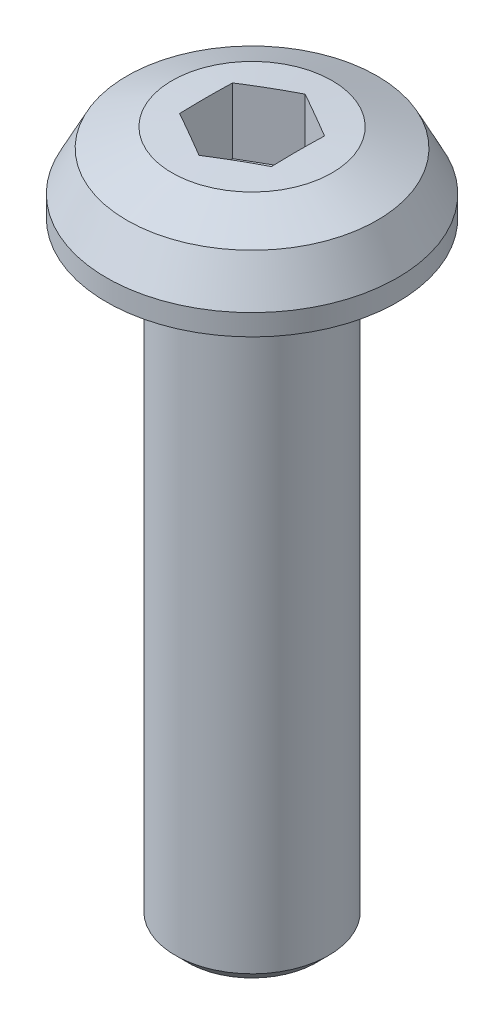
SolidWorks part; units mm, degrees
ref_plane "Front Plane" through (0, 0, 0) normal (0, 0, 1) x (1, 0, 0)
ref_plane "Top Plane" through (0, 0, 0) normal (0, 1, 0) x (1, 0, 0)
ref_plane "Right Plane" through (0, 0, 0) normal (1, 0, 0) x (0, 0, -1)
sketch "Sketch1" plane through (0, 0, 0) normal (0, 0, 1) x (1, 0, 0)
  line L0 (0, -20) -> (2.1, -20)
  line L1 (2.1, -20) -> (2.5, -19.6)
  line L2 (2.5, -19.6) -> (2.5, 0)
  line L3 (2.5, 0) -> (4.75, 0)
  line L4 (4.75, 0) -> (4.75, 0.6875)
  line L5 (4.75, 0.6875) -> (4.085, 1.98)
  line L6 (4.085, 1.98) -> (2.6125, 2.585)
  line L7 (2.6125, 2.585) -> (0, 2.75)
  line L8 (0, 2.75) -> (0, -20)
  line L9 (0, -10) -> (0, 1000) construction
revolve "Revolve1" add sketch "Sketch1" angle 360 about L9
cosmetic thread "Cosmetic Thread1" parameters "D1"=19.6, "D2"=4.134
ref_plane "Plane1" through (0, 2.75, 0) normal (0, 1, 0) x (1, 0, 0)
sketch "Sketch2" plane through (0, 2.75, 0) normal (0, 1, 0) x (1, 0, 0)
  line L0 (1.5, -0.866) -> (0, -1.7321)
  line L1 (0, -1.7321) -> (-1.5, -0.866)
  line L2 (-1.5, -0.866) -> (-1.5, 0.866)
  line L3 (-1.5, 0.866) -> (0, 1.7321)
  line L4 (0, 1.7321) -> (1.5, 0.866)
  line L5 (1.5, 0.866) -> (1.5, -0.866)
extrude "Cut-Extrude1" cut sketch "Sketch2" against normal blind 2.25
